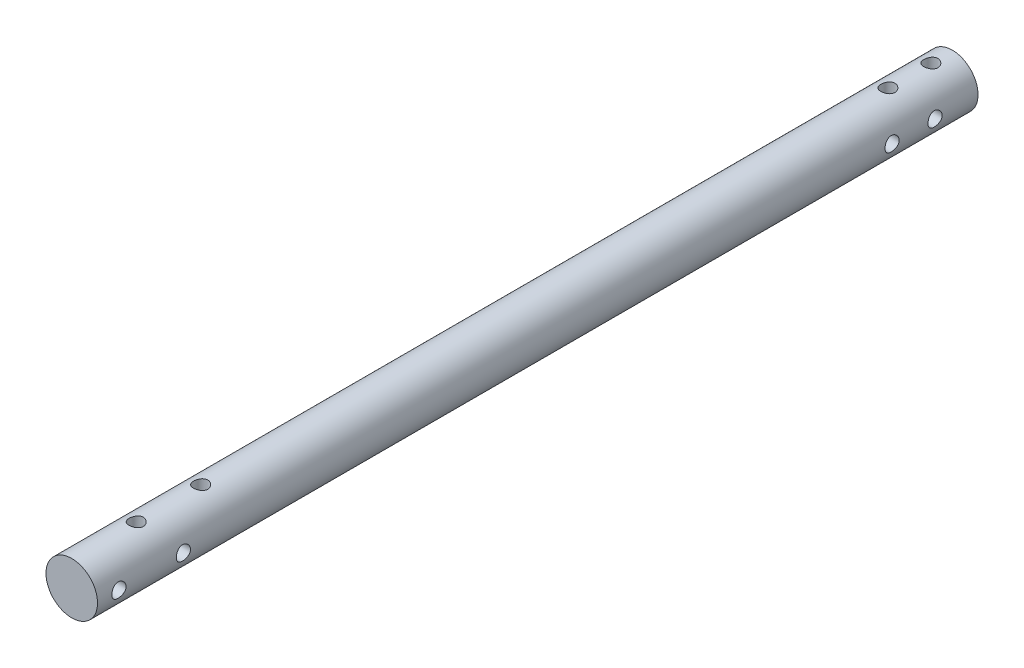
SolidWorks part; units mm, degrees
material "Thornel Mat VMA"
ref_plane "前视基准面" through (0, 0, 0) normal (0, 0, 1) x (1, 0, 0)
ref_plane "上视基准面" through (0, 0, 0) normal (0, 1, 0) x (1, 0, 0)
ref_plane "右视基准面" through (0, 0, 0) normal (1, 0, 0) x (0, 0, -1)
other "Configuration Table"
sketch "草图1" plane through (0, 0, 0) normal (0, 0, 1) x (1, 0, 0)
  line L1 (-4, 4) -> (4, 4)
  line L2 (-4, 4) -> (-4, -4)
  line L3 (-4, -4) -> (4, -4)
  line L4 (4, 4) -> (4, -4)
  line L5 (-4, 4) -> (4, -4) construction
  line L6 (-4, -4) -> (4, 4) construction
  line L7 (-2, 2) -> (2, 2)
  line L8 (-2, 2) -> (-2, -2)
  line L9 (-2, -2) -> (2, -2)
  line L10 (2, 2) -> (2, -2)
  line L11 (-2, 2) -> (2, -2) construction
  line L12 (-2, -2) -> (2, 2) construction
  point P0 (0, 0)
  point P6 (0, 0)
  dimension "D1" = 2
  dimension "D2" = 8
  dimension "D3" = 8
extrude "凸台-拉伸1" add sketch "草图1" along normal blind 205
sketch "草图7" plane through (0, 0, 0) normal (0, 0, -1) x (-1, 0, 0)
  circle A0 centre (0, 0) radius 6
  dimension "D1" = 12
extrude "凸台-拉伸2" add sketch "草图7" against normal blind 205
sketch "草图2" plane through (0, 0, 0) normal (0, 1, 0) x (1, 0, 0)
  line L1 (6, 0) -> (-6, 0) construction
  circle A0 centre (0, -5) radius 1.65
  circle A1 centre (0, -15) radius 1.65
  dimension "D1" = 10
  dimension "D2" = 3.3
  dimension "D3" = 5
extrude "切除-拉伸1" cut sketch "草图2" against normal through all both and the other way through all
sketch "草图3" plane through (0, 0, 0) normal (-1, 0, 0) x (0, 0, 1)
  line L0 (0, 0) -> (23.2715, 0) construction
  line L2 (10, 0) -> (20, 0) construction
  line L3 (0, 6) -> (0, -6) construction
  circle A1 centre (10, 0) radius 1.65
  circle A2 centre (20, 0) radius 1.65
  dimension "D1" = 3.3
  dimension "D2" = 2
  dimension "D3" = 10
  dimension "D4" = 10
extrude "切除-拉伸2" cut sketch "草图3" against normal through all both and the other way through all
sketch "草图4" plane through (0, 0, 0) normal (-1, 0, 0) x (0, 0, 1)
  line L1 (205, -6) -> (205, 6) construction
  circle A0 centre (200, 0) radius 1.65
  circle A1 centre (185, 0) radius 1.65
  dimension "D1" = 5
  dimension "D2" = 15
  dimension "D3" = 3.3
extrude "切除-拉伸3" cut sketch "草图4" against normal through all both and the other way through all
sketch "草图5" plane through (0, 0, 0) normal (0, 1, 0) x (1, 0, 0)
  line L1 (-6, -205) -> (6, -205) construction
  circle A0 centre (0, -190) radius 1.65
  circle A1 centre (0, -175) radius 1.65
  dimension "D1" = 15
  dimension "D2" = 15
  dimension "D3" = 3.3
extrude "切除-拉伸4" cut sketch "草图5" against normal through all both and the other way through all
sketch "草图8" plane through (0, 0, 0) normal (1, 0, 0) x (0, 0, -1)
  line L1 (-205, 6) -> (0, 6)
  line L2 (-205, 6) -> (-205, -6)
  line L3 (-205, -6) -> (0, -6)
  line L4 (0, 6) -> (0, -6)
  circle A0 centre (-20, 0) radius 1.65 construction
  circle A1 centre (-10, 0) radius 1.65 construction
  circle A2 centre (-185, 0) radius 1.65 construction
  circle A3 centre (-200, 0) radius 1.65 construction
  circle A4 centre (-20, 0) radius 1.65
  circle A5 centre (-10, 0) radius 1.65
  circle A6 centre (-185, 0) radius 1.65
  circle A7 centre (-200, 0) radius 1.65
extrude "凸台-拉伸3" [suppressed] add sketch "草图8" along normal blind 10
sketch "草图10" plane through (0, 0, 0) normal (0, 1, 0) x (1, 0, 0)
  line L0 (6, 0) -> (-6, 0) construction
  line L1 (-6, 0) -> (6, 0)
  line L2 (-6, 0) -> (-6, -205)
  line L3 (-6, -205) -> (6, -205)
  line L4 (6, 0) -> (6, -205)
  circle A0 centre (0, -5) radius 1.65 construction
  circle A1 centre (0, -190) radius 1.65 construction
  circle A2 centre (0, -175) radius 1.65 construction
  circle A3 centre (0, -15) radius 1.65 construction
  circle A4 centre (0, -190) radius 1.65
  circle A5 centre (0, -175) radius 1.65
  circle A6 centre (0, -15) radius 1.65
  circle A7 centre (0, -5) radius 1.65
extrude "凸台-拉伸4" [suppressed] add sketch "草图10" along normal blind 10
